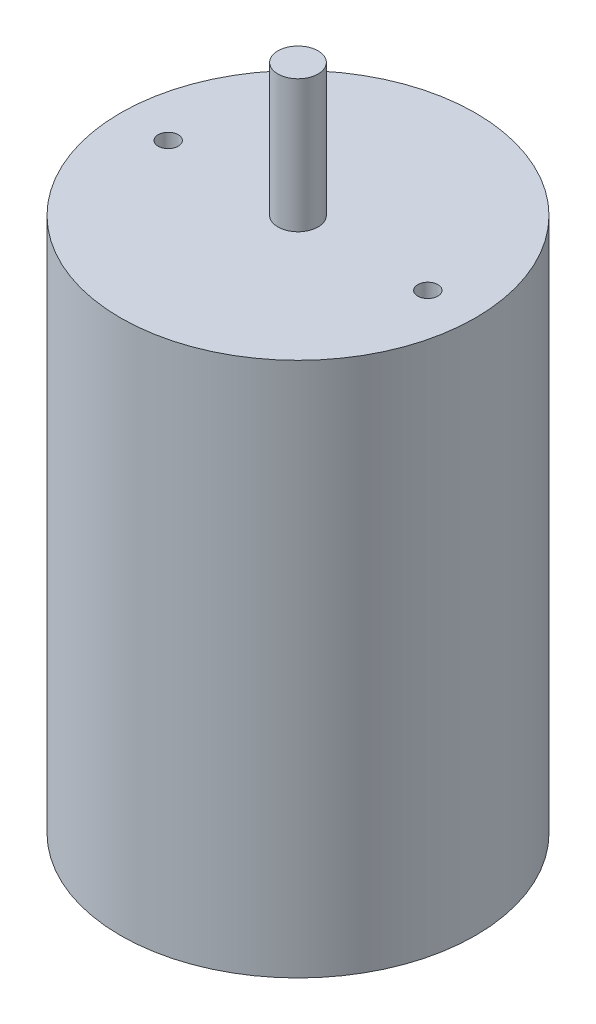
SolidWorks part; units mm, degrees
ref_plane "前基準面" through (0, 0, 0) normal (0, 0, 1) x (1, 0, 0)
ref_plane "上基準面" through (0, 0, 0) normal (0, 1, 0) x (1, 0, 0)
ref_plane "右基準面" through (0, 0, 0) normal (1, 0, 0) x (0, 0, -1)
sketch "草圖1" plane through (0, 0, 0) normal (0, 1, 0) x (1, 0, 0)
  circle A0 centre (0, 0) radius 22.1
  dimension "D1" = 44.2
extrude "填料-伸長1" add sketch "草圖1" along normal blind 66.6
sketch "草圖2" plane through (0, 66.6, 0) normal (0, 1, 0) x (1, 0, 0)
  circle A0 centre (0, 0) radius 2.5
  dimension "D1" = 5
extrude "填料-伸長2" add sketch "草圖2" along normal blind 16.5
sketch "草圖3" plane through (0, 0, 0) normal (0, -1, 0) x (1, 0, 0)
  circle A0 centre (0, 0) radius 2.5
  dimension "D1" = 5
extrude "填料-伸長3" add sketch "草圖3" along normal blind 5
sketch "草圖4" plane through (0, 66.6, 0) normal (0, 1, 0) x (1, 0, 0)
  line L0 (-25.8487, 0) -> (24.9038, 0) construction
  circle A0 centre (-16.165, 0) radius 1.25
  circle A1 centre (16.165, 0) radius 1.25
  dimension "D1" = 32.33
  dimension "D2" = 2.5
  dimension "D3" = 16.165
extrude "除料-伸長1" cut sketch "草圖4" against normal blind 5
